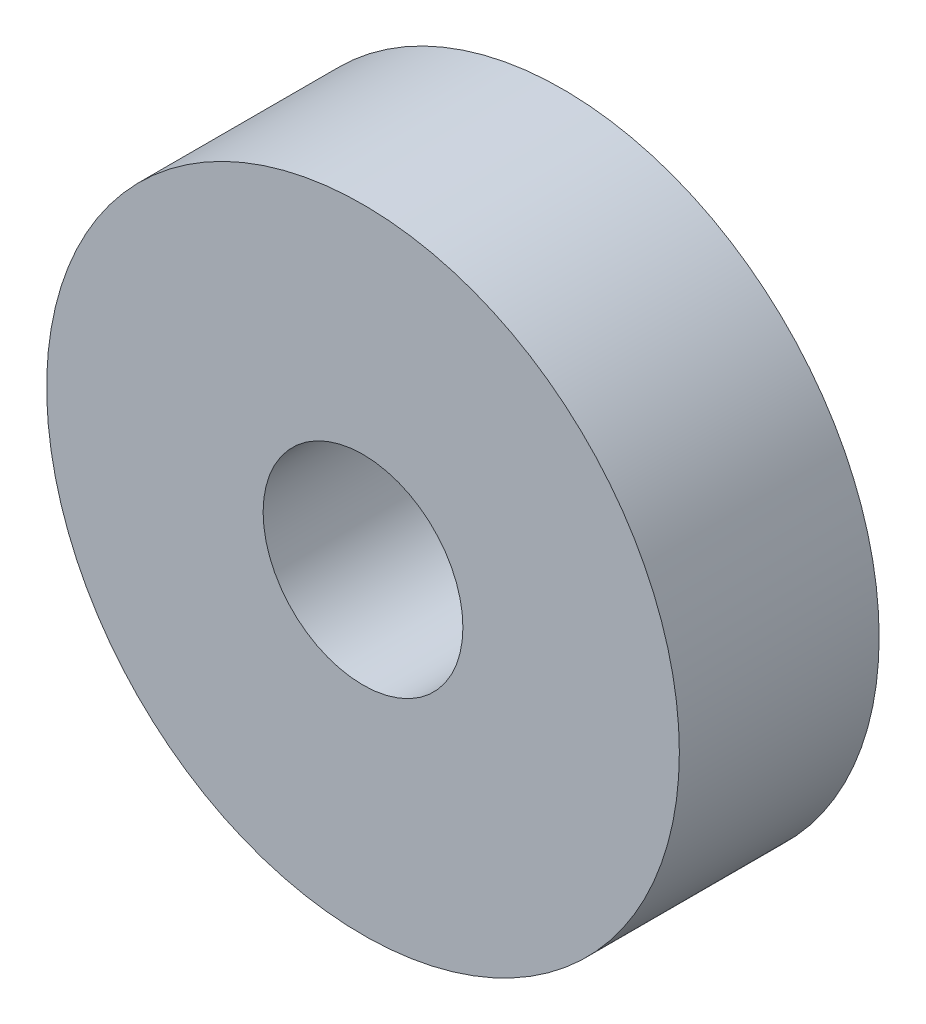
SolidWorks part; units mm, degrees
ref_plane "Спереди" through (0, 0, 0) normal (0, 0, 1) x (1, 0, 0)
ref_plane "Сверху" through (0, 0, 0) normal (0, 1, 0) x (1, 0, 0)
ref_plane "Справа" through (0, 0, 0) normal (1, 0, 0) x (0, 0, -1)
sketch "Эскиз1" plane through (0, 0, 0) normal (0, 1, 0) x (1, 0, 0)
  line L0 (-3, 0) -> (-9.5, 0)
  line L1 (-9.5, 0) -> (-9.5, 6)
  line L2 (-9.5, 6) -> (-3, 6)
  line L3 (-3, 6) -> (-3, 0)
  line L4 (0, 0) -> (0, 12201.6936) construction
  circle A0 centre (-5.75, 3) radius 1.5
  dimension "D4" = 3
  dimension "D1" = 3
  dimension "D2" = 9.5
  dimension "D3" = 6
  dimension "D5" = 5.75
  dimension "D6" = 3
revolve "Повернуть1" add sketch "Эскиз1" angle 360 about L4
